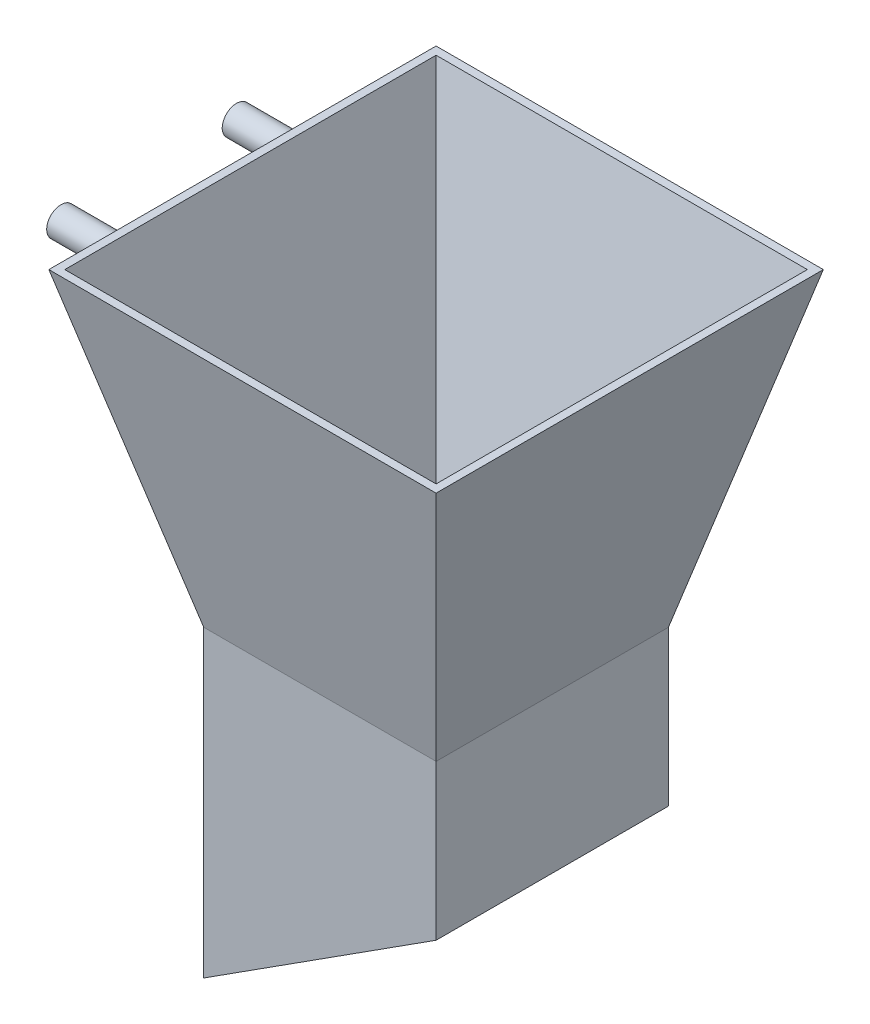
SolidWorks part; units mm, degrees
ref_plane "Alzado" through (0, 0, 0) normal (0, 0, 1) x (1, 0, 0)
ref_plane "Planta" through (0, 0, 0) normal (0, 1, 0) x (1, 0, 0)
ref_plane "Vista lateral" through (0, 0, 0) normal (1, 0, 0) x (0, 0, -1)
sketch "Croquis2" plane through (0, 0, 0) normal (0, 1, 0) x (1, 0, 0)
  line L1 (0, 0) -> (500, 0)
  line L2 (0, 0) -> (0, 500)
  line L3 (0, 500) -> (500, 500)
  line L4 (500, 0) -> (500, 500)
  dimension "D1" = 500
  dimension "D2" = 500
ref_plane "Plano1" through (0, -400, 0) normal (0, 1, 0) x (1, 0, 0)
sketch "Croquis3" plane through (0, -400, 0) normal (0, 1, 0) x (1, 0, 0)
  line L0 (250, 500) -> (250, 0) construction
  line L1 (0, 500) -> (500, 500) construction
  line L2 (0, 0) -> (500, 0) construction
  line L3 (250, 0) -> (500, 250) construction
  line L4 (500, 0) -> (500, 500) construction
  line L5 (500, 250) -> (0, 250) construction
  line L6 (0, 0) -> (0, 500) construction
  line L8 (100, 400) -> (400, 400)
  line L9 (100, 400) -> (100, 100)
  line L10 (100, 100) -> (400, 100)
  line L11 (400, 400) -> (400, 100)
  line L12 (100, 400) -> (400, 100) construction
  line L13 (100, 100) -> (400, 400) construction
  point P12 (250, 250)
  dimension "D1" = 300
  dimension "D2" = 300
loft "Recubrir1" add profiles "Croquis2", "Croquis3"
sketch "Croquis4" plane through (0, -400, 0) normal (0, -1, 0) x (1, 0, 0)
  line L1 (100, -100) -> (400, -100)
  line L2 (100, -100) -> (100, -400)
  line L3 (100, -400) -> (400, -400)
  line L4 (400, -100) -> (400, -400)
  line L5 (100, -100) -> (400, -400) construction
  line L6 (100, -400) -> (400, -100) construction
  point P0 (250, -250)
extrude "Saliente-Extruir1" add sketch "Croquis4" along normal blind 200
sketch "Croquis5" plane through (0, 0, -100) normal (0, 0, 1) x (1, 0, 0)
  line L0 (100, -600) -> (100, -792.1752)
  line L1 (100, -792.1752) -> (400, -600)
  line L2 (400, -600) -> (100, -600) construction
  line L3 (100, -600) -> (400, -600)
extrude "Saliente-Extruir2" add sketch "Croquis5" against normal up to surface (300 mm away) up to face at (287.5, -550, -400)
shell "Vaciado1" thickness 10
ref_plane "Plano2" through (0, 0, 0) normal (1, 0, 0) x (0, 0, -1)
sketch "Croquis6" plane through (0, 0, 0) normal (1, 0, 0) x (0, 0, -1)
  line L0 (250, -50) -> (250, -100) construction
  line L3 (550, -50) -> (-50, -50) construction
  line L4 (-50, -100) -> (550, -100) construction
  line L5 (250, -100) -> (363.3171, -100) construction
  line L6 (363.3171, -100) -> (363.3171, -50) construction
  circle A0 centre (363.3171, -74.7254) radius 18.4816
  circle A1 centre (136.6829, -74.7254) radius 18.4816
extrude "Saliente-Extruir3" add sketch "Croquis6" along normal blind 10 and the other way blind 121 separate body
